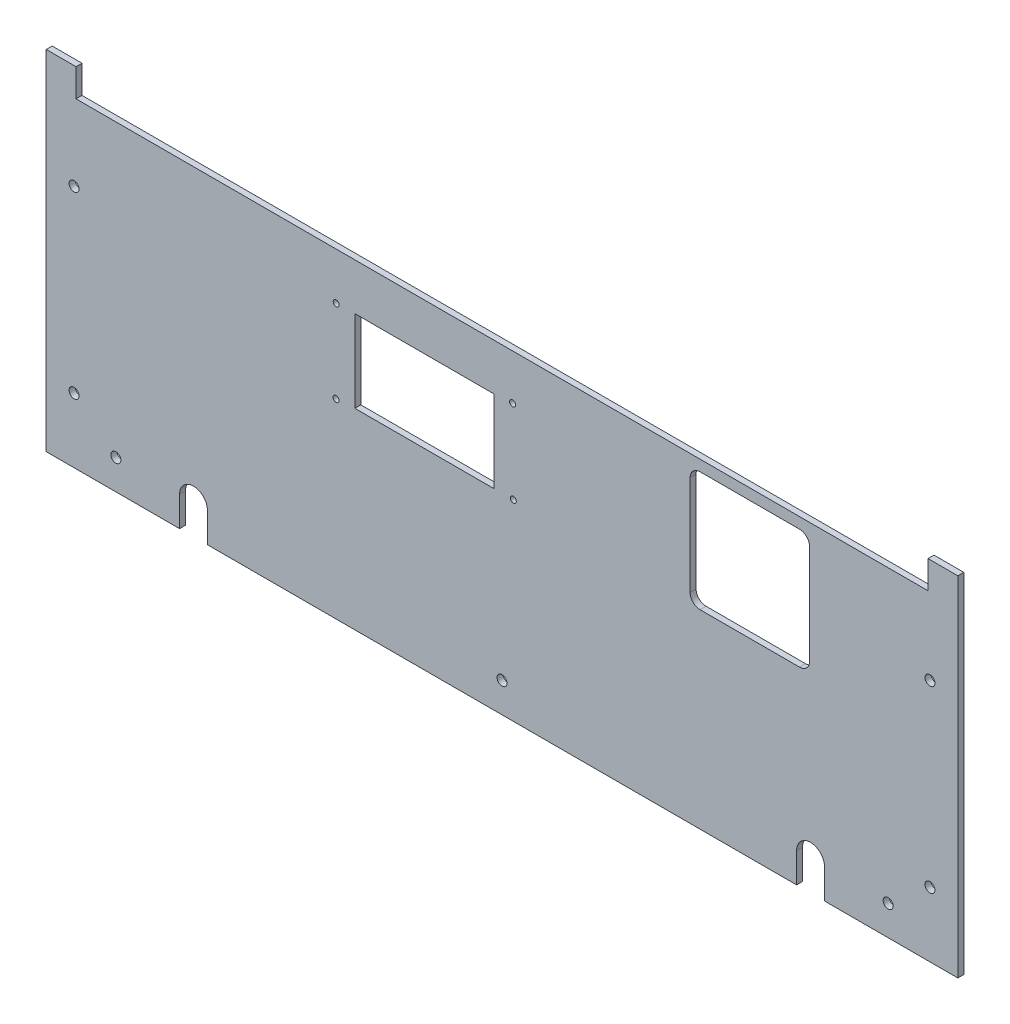
SolidWorks part; units mm, degrees
material "1345 Alloy"
ref_plane "Front Plane" through (0, 0, 0) normal (0, 0, 1) x (1, 0, 0)
ref_plane "Top Plane" through (0, 0, 0) normal (0, 1, 0) x (1, 0, 0)
ref_plane "Right Plane" through (0, 0, 0) normal (1, 0, 0) x (0, 0, -1)
sketch "Sketch1" plane through (0, 0, 0) normal (0, 0, 1) x (1, 0, 0)
  line L1 (-229, 122.5) -> (229, 122.5)
  line L2 (-229, 122.5) -> (-229, -122.5)
  line L3 (-229, -122.5) -> (229, -122.5)
  line L4 (229, 122.5) -> (229, -122.5)
  line L5 (-229, 122.5) -> (229, -122.5) construction
  line L6 (-229, -122.5) -> (229, 122.5) construction
  point P0 (0, 0)
  dimension "D1" = 458
  dimension "D2" = 245
extrude "Boss-Extrude1" add sketch "Sketch1" along normal blind 3
sketch "Sketch2" plane through (0, 0, 3) normal (0, 0, 1) x (1, 0, 0)
  line L0 (-229, -122.5) -> (-155, -122.5) construction
  line L2 (-155, -122.5) -> (-155, -107.5) construction
  line L3 (-155, -107.5) -> (-155, -122.5) construction
  line L6 (-148, -107.5) -> (-148, -122.5)
  line L11 (-162, -107.5) -> (-162, -122.5)
  line L12 (155, -122.5) -> (229, -122.5) construction
  line L13 (155, -107.5) -> (155, -122.5) construction
  line L14 (162, -107.5) -> (162, -122.5)
  line L15 (148, -107.5) -> (148, -122.5)
  line L16 (-155, -107.5) -> (155, -107.5) construction
  arc A4 (-148, -107.5) -> (-162, -107.5) centre (-155, -107.5) ccw
  arc A5 (-162, -122.5) -> (-148, -122.5) centre (-155, -122.5) ccw
  arc A6 (162, -107.5) -> (148, -107.5) centre (155, -107.5) ccw
  arc A7 (148, -122.5) -> (162, -122.5) centre (155, -122.5) ccw
  point P4 (-155, -115)
  point P13 (155, -115)
  dimension "D3" = 7
  dimension "D5" = 7
  dimension "D1" = 74
  dimension "D2" = 15
  dimension "D4" = 15
  dimension "D6" = 74
extrude "Cut-Extrude1" cut sketch "Sketch2" against normal through all
sketch "Sketch3" plane through (0, 0, 3) normal (0, 0, 1) x (1, 0, 0)
  line L19 (194, 112.5) -> (194, -107.5) construction
  line L20 (-215, 0) -> (-215, 90) construction
  line L21 (-215, 0) -> (-215, -90) construction
  line L25 (229, 0) -> (215, 0) construction
  line L26 (0, 112.5) -> (-194, 112.5) construction
  line L27 (-194, 112.5) -> (-194, -107.5) construction
  line L31 (215, 0) -> (215, 90) construction
  line L32 (215, 0) -> (215, -90) construction
  line L33 (0, 112.5) -> (194, 112.5) construction
  line L34 (0, 0) -> (0, 112.5) construction
  line L35 (0, 0) -> (0, -107.5) construction
  line L36 (-194, -107.5) -> (0, -107.5) construction
  line L37 (0, -107.5) -> (194, -107.5) construction
  line L38 (-194, 112.5) -> (-229, 112.5) construction
  line L39 (-229, 112.5) -> (-229, 122.5) construction
  circle A12 centre (-194, 112.5) radius 2.5
  circle A13 centre (-194, -107.5) radius 2.5
  circle A14 centre (194, -107.5) radius 2.5
  circle A15 centre (194, 112.5) radius 2.5
  circle A16 centre (-215, 0) radius 2.5
  circle A17 centre (-215, -90) radius 2.5
  circle A18 centre (-215, 90) radius 2.5
  circle A19 centre (215, 0) radius 2.5
  circle A20 centre (215, -90) radius 2.5
  circle A21 centre (215, 90) radius 2.5
  circle A22 centre (0, 112.5) radius 2.5
  circle A23 centre (0, -107.5) radius 2.5
  dimension "D3" = 5
  dimension "D6" = 90
  dimension "D9" = 5
  dimension "D12" = 90
  dimension "D15" = 5
  dimension "D16" = 194
  dimension "D17" = 194
  dimension "D2" = 5
  dimension "D4" = 5
  dimension "D5" = 5
  dimension "D8" = 5
  dimension "D10" = 5
  dimension "D14" = 5
  dimension "D7" = 90
  dimension "D11" = 14
  dimension "D13" = 90
  dimension "D18" = 194
  dimension "D19" = 194
extrude "Cut-Extrude2" cut sketch "Sketch3" against normal through all
sketch "Sketch4" plane through (0, 0, 3) normal (0, 0, 1) x (1, 0, 0)
  line L5 (0, 122.5) -> (0, 102.5) construction
  line L6 (229, 122.5) -> (-229, 122.5) construction
  line L7 (0, 102.5) -> (0, 82.5) construction
  line L8 (229, 91) -> (39, 91) construction
  line L10 (-39, 102.5) -> (-39, 122.5) construction
  line L11 (229, -122.5) -> (229, 122.5) construction
  line L12 (-229, 91) -> (-39, 91) construction
  line L13 (-229, 122.5) -> (-229, -122.5) construction
  line L14 (-39, 91) -> (0, 91) construction
  circle A1 centre (-39, 91) radius 11.5
  circle A2 centre (39, 91) radius 11.5
  dimension "D6" = 190
  dimension "D4" = 23
  dimension "D7" = 23
  dimension "D1" = 20
  dimension "D2" = 20
  dimension "D3" = 20
  dimension "D5" = 190
extrude "Cut-Extrude3" cut sketch "Sketch4" against normal through all
sketch "Sketch5" plane through (0, 0, 3) normal (0, 0, 1) x (1, 0, 0)
  line L0 (-229, -122) -> (-229, 53) construction
  line L1 (-229, 53) -> (229, 53) construction
  line L2 (-229, 53) -> (-229, 67.5) construction
  line L3 (-229, 67.5) -> (-214, 67.5) construction
  line L4 (229, 53) -> (229, 67.5) construction
  line L5 (229, 67.5) -> (214, 67.5) construction
  line L6 (214, 67.5) -> (-214, 67.5)
  line L7 (-214, 67.5) -> (-214, 38.5)
  line L8 (-214, 38.5) -> (214, 38.5)
  line L9 (214, 38.5) -> (214, 67.5)
  dimension "D1" = 175
  dimension "D2" = 14.5
  dimension "D3" = 15
  dimension "D4" = 14.5
  dimension "D5" = 15
  dimension "D6" = 29
extrude "Cut-Extrude4" cut sketch "Sketch5" against normal through all
sketch "Sketch8" plane through (0, 0, 3) normal (0, 0, 1) x (1, 0, 0)
  line L0 (-39, -5.5) -> (-39, 79.5) construction
  line L1 (-73.95, 15.1) -> (-4.05, 15.1)
  line L2 (-73.95, 15.1) -> (-73.95, -26.1)
  line L3 (-73.95, -26.1) -> (-4.05, -26.1)
  line L4 (-4.05, 15.1) -> (-4.05, -26.1)
  line L5 (-73.95, 15.1) -> (-4.05, -26.1) construction
  line L6 (-73.95, -26.1) -> (-4.05, 15.1) construction
  line L12 (5.6797, -26.0547) -> (-83.3, 14.88) construction
  line L13 (5.2962, 15.7036) -> (-83.368, -26.7379) construction
  circle A1 centre (-39, 91) radius 11.5 construction
  circle A2 centre (5.2962, 15.7036) radius 1.5
  circle A3 centre (5.6797, -26.0547) radius 1.5
  circle A4 centre (-83.3, 14.88) radius 1.5
  circle A5 centre (-83.368, -26.7379) radius 1.5
  point P0 (-39, -5.5)
  dimension "D6" = 3
  dimension "D7" = 3
  dimension "D8" = 3
  dimension "D9" = 3
  dimension "D1" = 69.9
  dimension "D2" = 41.2
  dimension "D3" = 85
  dimension "D4" = 88.6
  dimension "D5" = 41.76
extrude "Cut-Extrude5" cut sketch "Sketch8" against normal through all
sketch "Sketch9" plane through (0, 0, 3) normal (0, 0, 1) x (1, 0, 0)
  line L0 (-229, 122.5) -> (-229, 52.5) construction
  line L1 (-229, 122.5) -> (-229, -122.5) construction
  line L3 (-229, 52.5) -> (229, 52.5)
  line L4 (-229, 52.5) -> (-229, 122.5)
  line L5 (-229, 122.5) -> (229, 122.5)
  line L6 (229, 52.5) -> (229, 122.5)
  dimension "D1" = 70
extrude "Cut-Extrude6" cut sketch "Sketch9" against normal blind 10
sketch "Sketch11" plane through (0, 0, 0) normal (0, 0, 1) x (1, 0, 0)
  line L0 (99.5, -27) -> (149.5, -27)
  line L1 (154.5, -22) -> (154.5, 28)
  line L2 (149.5, 33) -> (99.5, 33)
  line L3 (94.5, 28) -> (94.5, -22)
  arc A0 (149.5, -27) -> (154.5, -22) centre (149.5, -22) ccw
  arc A1 (154.5, 28) -> (149.5, 33) centre (149.5, 28) ccw
  arc A2 (99.5, 33) -> (94.5, 28) centre (99.5, 28) ccw
  arc A3 (94.5, -22) -> (99.5, -27) centre (99.5, -22) ccw
extrude "Cut_SwitchRubber_60x60" cut sketch "Sketch11" against normal through all and the other way through all
